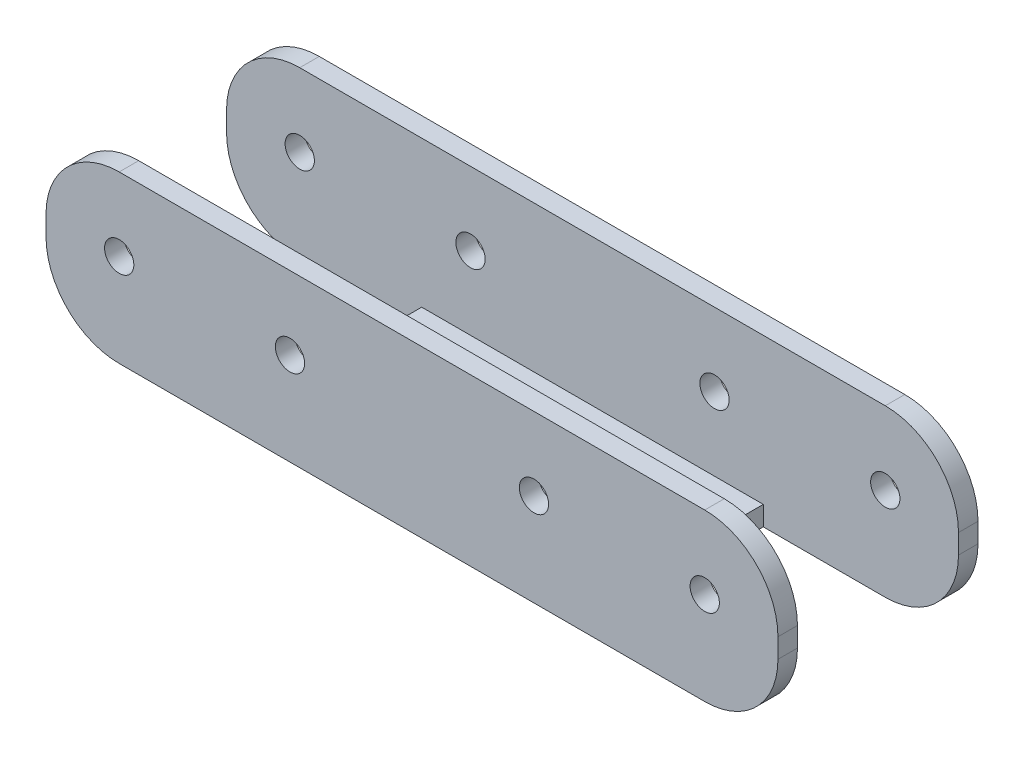
SolidWorks part; units mm, degrees
ref_plane "前视基准面" through (0, 0, 0) normal (0, 0, 1) x (1, 0, 0)
ref_plane "上视基准面" through (0, 0, 0) normal (0, 1, 0) x (1, 0, 0)
ref_plane "右视基准面" through (0, 0, 0) normal (1, 0, 0) x (0, 0, -1)
sketch "草图1" plane through (0, 0, 0) normal (1, 0, 0) x (0, 0, -1)
  line L0 (0, 43.3361) -> (0, -38.7973) construction
  line L1 (-16.5, 34) -> (-20.5, 34)
  line L2 (-20.5, 34) -> (-20.5, 0)
  line L3 (-20.5, 0) -> (20.5, 0)
  line L4 (0, 0) -> (0, 4)
  line L5 (16.5, 4) -> (-16.5, 4)
  line L6 (-16.5, 4) -> (-16.5, 34)
  line L7 (16.5, 4) -> (16.5, 34)
  line L8 (20.5, 34) -> (20.5, 0)
  line L9 (16.5, 34) -> (20.5, 34)
  dimension "D1" = 4
  dimension "D2" = 4
  dimension "D3" = 16.5
  dimension "D4" = 30
extrude "凸台-拉伸1" add sketch "草图1" along normal blind 150 contours L5 L6 L1 L2 L3 L4 | L9 L7 L5 L4 L3 L8
sketch "草图2" plane through (0, 0, 20.5) normal (0, 0, 1) x (1, 0, 0)
  line L0 (75, 34) -> (75, -88.1355) construction
  line L1 (150, 34) -> (0, 34) construction
  line L2 (150, 4) -> (0, 4) construction
  circle A0 centre (15, 19) radius 3
  circle A1 centre (135, 19) radius 3
  dimension "D1" = 6
  dimension "D2" = 60
  dimension "D3" = 15
extrude "切除-拉伸1" cut sketch "草图2" against normal blind 300
sketch "草图3" plane through (0, 0, 0) normal (0, -1, 0) x (1, 0, 0)
  line L0 (150, 16.5) -> (150, -16.5)
  line L1 (150, 20.5) -> (150, -20.5) construction
  line L2 (150, -16.5) -> (110, -16.5)
  line L3 (110, -16.5) -> (110, 16.5)
  line L4 (110, 16.5) -> (150, 16.5)
  line L5 (150, 20.5) -> (0, 20.5) construction
  line L6 (150, -20.5) -> (0, -20.5) construction
  line L7 (75, 20.5) -> (75, -125.7176) construction
  line L8 (40, 16.5) -> (0, 16.5)
  line L9 (40, -16.5) -> (40, 16.5)
  line L10 (0, -16.5) -> (40, -16.5)
  line L11 (0, 16.5) -> (0, -16.5)
  dimension "D1" = 4
  dimension "D2" = 4
  dimension "D3" = 40
extrude "切除-拉伸2" cut sketch "草图3" against normal blind 10
fillet "圆角1" radius 15 8 edges at (0, 0, 18.5) (0, 34, 18.5) (150, 34, 18.5) (150, 0, 18.5) (150, 34, -18.5) (150, 0, -18.5) (0, 0, -18.5) (0, 34, -18.5)
sketch "草图4" plane through (0, 0, 20.5) normal (0, 0, 1) x (1, 0, 0)
  line L0 (110, 4) -> (40, 4) construction
  circle A0 centre (50, 19) radius 3
  circle A1 centre (15, 19) radius 3 construction
  circle A2 centre (100, 19) radius 3
  circle A3 centre (135, 19) radius 3 construction
  dimension "D1" = 6
  dimension "D2" = 35
  dimension "D3" = 6
  dimension "D4" = 35
  dimension "D5" = 15
  dimension "D6" = 15
extrude "切除-拉伸3" cut sketch "草图4" against normal through all
